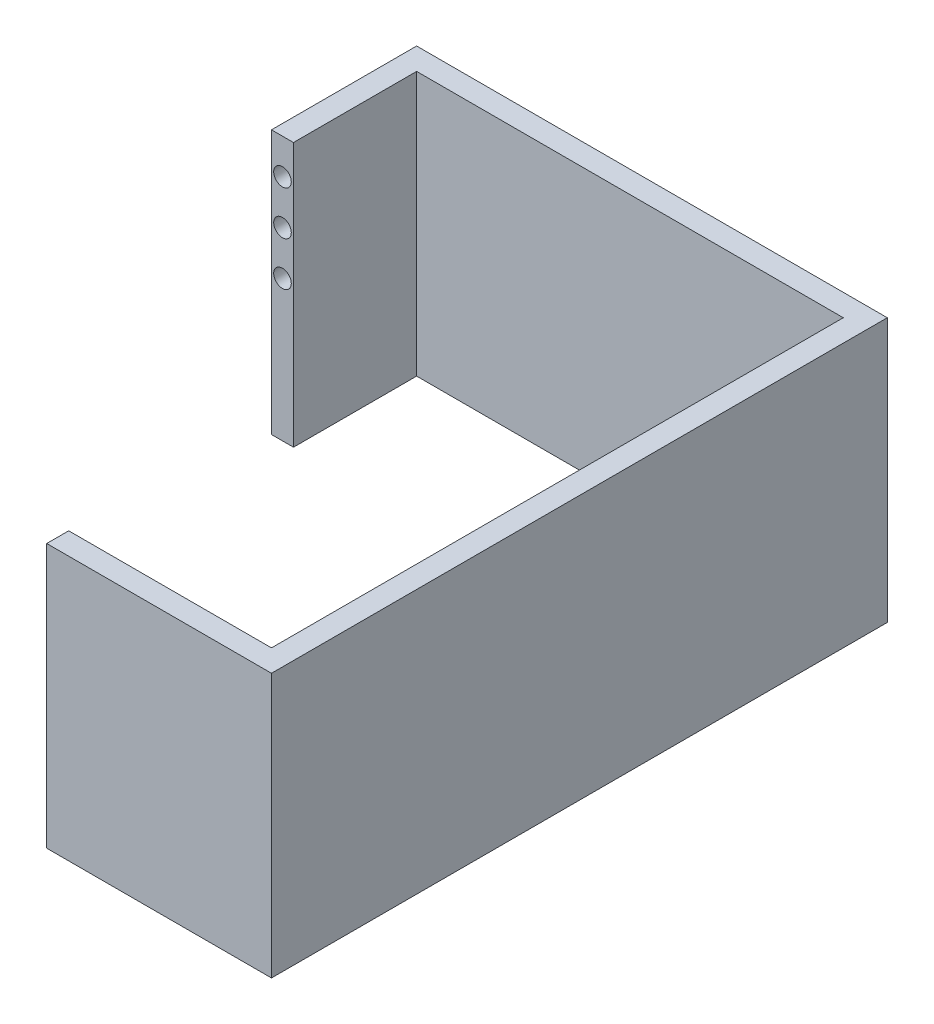
SolidWorks part; units mm, degrees
ref_plane "Front Plane" through (0, 0, 0) normal (0, 0, 1) x (1, 0, 0)
ref_plane "Top Plane" through (0, 0, 0) normal (0, 1, 0) x (1, 0, 0)
ref_plane "Right Plane" through (0, 0, 0) normal (1, 0, 0) x (0, 0, -1)
sketch "Sketch1" plane through (0, 0, 0) normal (0, 1, 0) x (1, 0, 0)
  line L1 (30.7626, 167.2245) -> (37.1126, 167.2245)
  line L2 (30.7626, 167.2245) -> (30.7626, -10.5755)
  line L3 (30.7626, -10.5755) -> (37.1126, -10.5755)
  line L4 (37.1126, 167.2245) -> (37.1126, -10.5755)
  line L5 (30.7626, -10.5755) -> (-27.7844, -10.5755)
  line L6 (30.7626, -10.5755) -> (30.7626, -4.2255)
  line L7 (30.7626, -4.2255) -> (-27.7844, -4.2255)
  line L8 (-27.7844, -10.5755) -> (-27.7844, -4.2255)
  line L9 (30.7626, 167.2245) -> (-98.7774, 167.2245)
  line L10 (30.7626, 167.2245) -> (30.7626, 160.8745)
  line L11 (30.7626, 160.8745) -> (-98.7774, 160.8745)
  line L12 (-98.7774, 167.2245) -> (-98.7774, 160.8745)
  line L13 (-98.7774, 160.8745) -> (-92.4274, 160.8745)
  line L14 (-98.7774, 160.8745) -> (-98.7774, 125.3145)
  line L15 (-98.7774, 125.3145) -> (-92.4274, 125.3145)
  line L16 (-92.4274, 160.8745) -> (-92.4274, 125.3145)
  dimension "D1" = 6.35
  dimension "D2" = 177.8
  dimension "D3" = 6.35
  dimension "D4" = 58.547
  dimension "D5" = 129.54
  dimension "D6" = 6.35
  dimension "D7" = 6.35
  dimension "D8" = 35.56
extrude "Boss-Extrude1" add sketch "Sketch1" along normal blind 76.2 contours L8 L5 L2 L7 | L4 L1 L2 L3 | L9 L12 L11 L2 | L16 L11 L14 L15
sketch "Sketch4" plane through (-27.7844, 0, 0) normal (-1, 0, 0) x (0, 0, 1)
  line L0 (10.5755, 76.2) -> (10.5755, 0) construction
  line L2 (10.5755, 76.2) -> (4.2255, 76.2) construction
  circle A0 centre (7.4005, 66.04) radius 2.54
  circle A1 centre (7.4005, 53.34) radius 2.54
  circle A2 centre (7.4005, 40.64) radius 2.54
  dimension "D1" = 5.08
  dimension "D2" = 3.175
  dimension "D3" = 10.16
  dimension "D4" = 3
extrude "Cut-Extrude2" cut sketch "Sketch4" against normal blind 25.4
sketch "Sketch6" plane through (0, 0, -125.3145) normal (0, 0, 1) x (1, 0, 0)
  line L0 (-98.7774, 76.2) -> (-98.7774, 0) construction
  line L1 (-98.7774, 76.2) -> (-92.4274, 76.2) construction
  line L2 (-95.6024, 66.04) -> (-95.6024, 53.34) construction
  circle A0 centre (-95.6024, 66.04) radius 2.54
  circle A1 centre (-95.6024, 53.34) radius 2.54
  circle A2 centre (-95.6024, 40.64) radius 2.54
  dimension "D1" = 5.08
  dimension "D3" = 10.16
  dimension "D2" = 3.175
  dimension "D4" = 12.7
extrude "Cut-Extrude4" cut sketch "Sketch6" against normal blind 25.4
